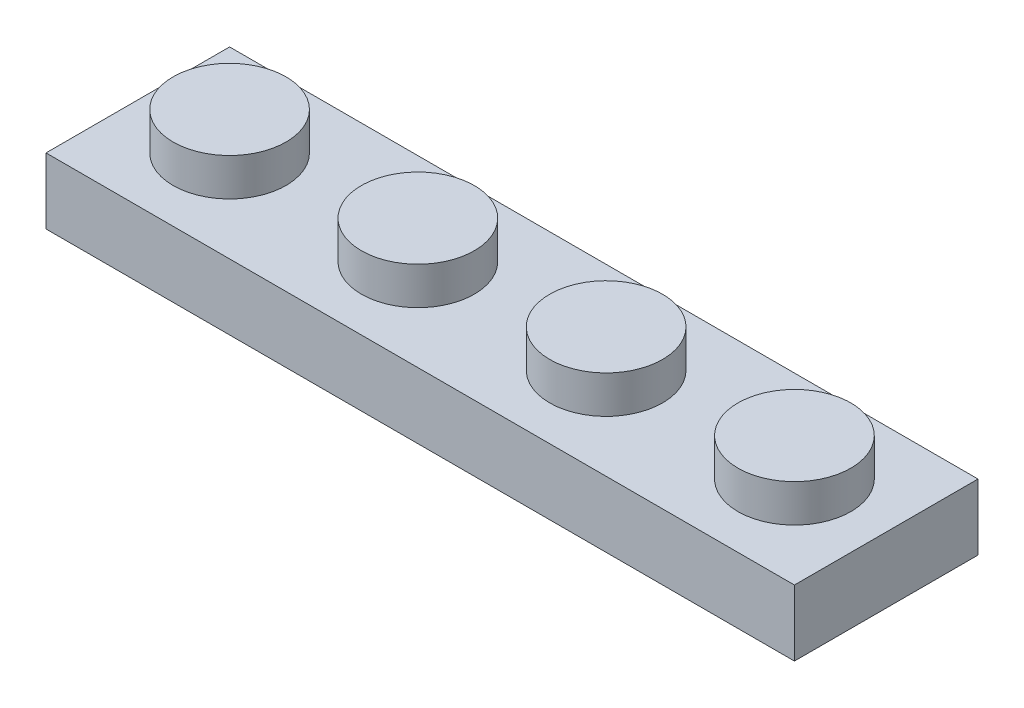
SolidWorks part; units mm, degrees
material "ABS"
ref_plane "Front Plane" through (0, 0, 0) normal (0, 0, 1) x (1, 0, 0)
ref_plane "Top Plane" through (0, 0, 0) normal (0, 1, 0) x (1, 0, 0)
ref_plane "Right Plane" through (0, 0, 0) normal (1, 0, 0) x (0, 0, -1)
sketch "Sketch1" plane through (0, 0, 0) normal (0, 0, 1) x (1, 0, 0)
  line L1 (0, 0) -> (31.8, 0)
  line L2 (0, 0) -> (0, 2.8)
  line L3 (0, 2.8) -> (31.8, 2.8)
  line L4 (31.8, 0) -> (31.8, 2.8)
  line L5 (0, 0) -> (31.8, 2.8) construction
  line L6 (0, 2.8) -> (31.8, 0) construction
  point P4 (15.9, 1.4)
  dimension "D1" = 31.8
  dimension "D2" = 2.8
extrude "Boss-Extrude1" add sketch "Sketch1" against normal blind 7.8
sketch "Sketch2" plane through (0, 2.8, 0) normal (0, 1, 0) x (1, 0, 0)
  line L0 (31.8, 0) -> (0, 0) construction
  circle A0 centre (3.9, 3.9) radius 2.4
  dimension "D1" = 4.8
  dimension "D2" = 3.9
  dimension "D3" = 3.9
extrude "Boss-Extrude2" add sketch "Sketch2" along normal blind 1.6
pattern_linear "LPattern1" count 2 spacing 8 along (0, 0, 1) count 4 spacing 8 along (1, 0, 0) of "Boss-Extrude2"
shell "Shell1" thickness 0.5
sketch "Sketch3" plane through (0, 2.3, 0) normal (0, -1, 0) x (1, 0, 0)
  line L0 (0, 0) -> (31.8, 0) construction
  line L1 (0, -7.8) -> (0, 0) construction
  circle A0 centre (7.9, -3.9) radius 1.15
  circle A1 centre (7.9, -3.9) radius 0.5
  dimension "D1" = 2.3
  dimension "D2" = 1
  dimension "D3" = 3.9
  dimension "D4" = 7.9
extrude "Boss-Extrude3" add sketch "Sketch3" along normal offset from surface (2.1 mm away) 0.2 up to face at (15.9, 0, -3.9)
pattern_linear "LPattern2" count 3 spacing 8 along (1, 0, 0) of "Boss-Extrude3"
